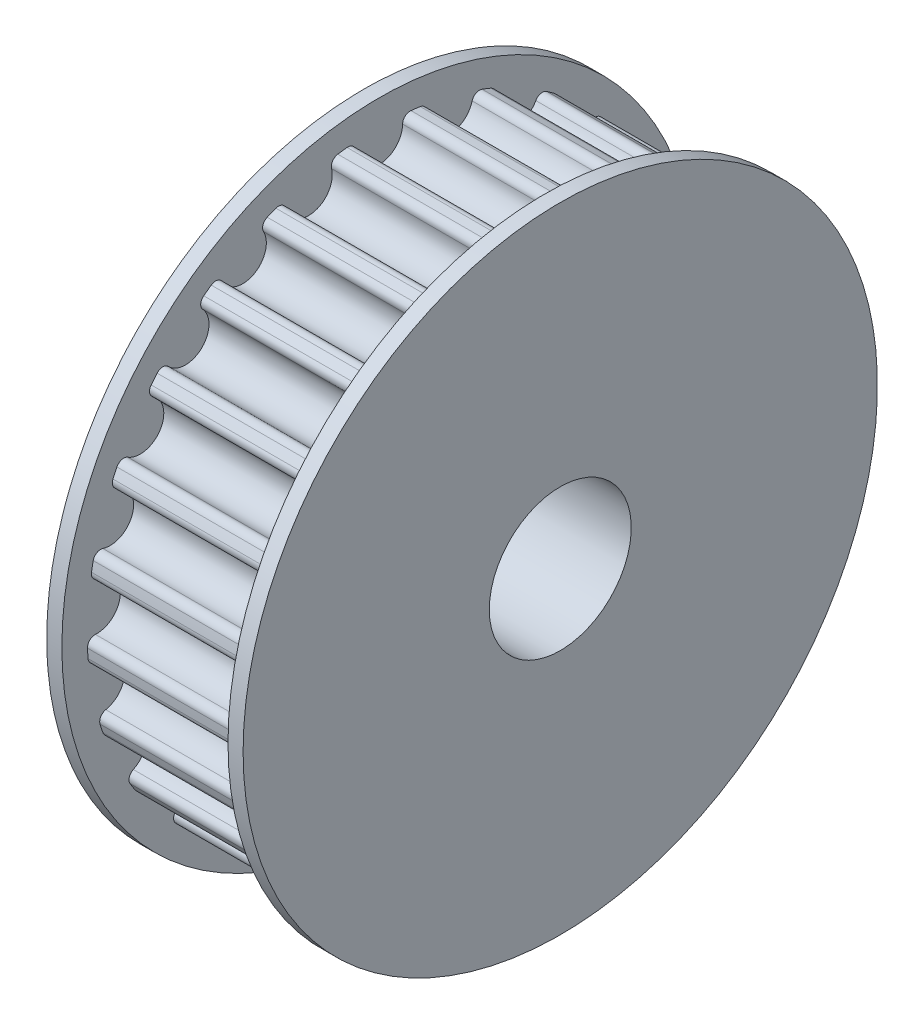
SolidWorks part; units mm, degrees
ref_plane "前视基准面" through (0, 0, 0) normal (0, 0, 1) x (1, 0, 0)
ref_plane "上视基准面" through (0, 0, 0) normal (0, 1, 0) x (1, 0, 0)
ref_plane "右视基准面" through (0, 0, 0) normal (1, 0, 0) x (0, 0, -1)
sketch "草图1" plane through (0, 0, 0) normal (0, 0, 1) x (1, 0, 0)
  line L0 (-8, 15) -> (-5.5, 15)
  line L1 (-5.5, 15) -> (-5.5, 19.325)
  line L2 (-5.5, 19.325) -> (5.5, 19.325)
  line L3 (0, 0) -> (0, 19.325) construction
  line L4 (-8, 15) -> (-8, 0)
  line L5 (8, 15) -> (8, 0)
  line L6 (5.5, 15) -> (5.5, 19.325)
  line L7 (8, 15) -> (5.5, 15)
  line L8 (-8, 0) -> (8, 0)
  dimension "D1" = 15
  dimension "D2" = 19.325
  dimension "D3" = 11
  dimension "D4" = 16
revolve "旋转1" add sketch "草图1" angle 360 about L8
sketch "草图3" plane through (0, 0, 0) normal (1, 0, 0) x (0, 0, -1)
  line L0 (0, 0) -> (0, 19.325) construction
  arc A0 (-2.1147, 19.209) -> (2.1147, 19.209) centre (0, 0) ccw
  circle A1 centre (0, 0) radius 19.325 construction
  arc A2 (-1.56, 18.7151) -> (1.56, 18.7151) centre (0, 18.725) ccw
  arc A3 (-1.56, 18.7151) -> (-2.1147, 19.209) centre (-2.06, 18.712) ccw
  arc A4 (2.1147, 19.209) -> (1.56, 18.7151) centre (2.06, 18.712) ccw
  point P5 (0, 17.165)
  point P11 (-1.4618, 19.2696)
  dimension "D4" = 0.5
  dimension "D1" = 2.16
  dimension "D2" = 1.56
  dimension "D5" = 0.5
extrude "切除-拉伸3" cut sketch "草图3" against normal mid plane 11 flip side to cut
pattern_circular "阵列(圆周)2" count 25 over 360 about axis through (0, 0, 0) along (1, 0, 0) of "切除-拉伸3"
sketch "草图4" plane through (0, 0, 0) normal (0, 0, 1) x (1, 0, 0)
  line L0 (-7, 22.5) -> (-7, 15)
  line L1 (-5.5, 15) -> (-8, 15) construction
  line L2 (7, 22.5) -> (7, 15)
  line L3 (-7, 22.5) -> (-5.9019, 22.5)
  line L4 (-5.9019, 22.5) -> (-5.5, 21)
  line L5 (-5.5, 21) -> (-5.5, 15)
  line L6 (-5.5, 15) -> (-7, 15)
  line L9 (0, 0) -> (0, 9.52) construction
  line L11 (-8, 0) -> (8, 0) construction
  line L12 (-8, 15) -> (-8, -15) construction
  line L13 (8, -15) -> (8, 15) construction
  line L14 (5.5, 21) -> (5.5, 15)
  line L15 (5.5, 15) -> (7, 15)
  line L17 (5.9019, 22.5) -> (5.5, 21)
  line L18 (7, 22.5) -> (5.9019, 22.5)
  dimension "D1" = 1.5
  dimension "D2" = 15
  dimension "D3" = 22.5
  dimension "D4" = 1.5
  dimension "D5" = 5.5
revolve "旋转2" add sketch "草图4" angle 360 about L11
sketch "草图5" plane through (0, 0, 0) normal (0, 0, 1) x (1, 0, 0)
  line L0 (8, -15) -> (8, 15) construction
  line L1 (8, 0) -> (20, 0)
  line L2 (8, 0) -> (8, 13.5)
  line L3 (8, 13.5) -> (20, 13.5)
  line L4 (20, 0) -> (20, 13.5)
  dimension "D1" = 13.5
  dimension "D2" = 12
revolve "旋转3" [suppressed] add sketch "草图5" angle 360 about L1
sketch "草图37" [suppressed] plane through (0, 0, 0) normal (0, 0, 1) x (1, 0, 0)
  line L0 (-8, 0) -> (8, 0) construction
  line L1 (-7.5, 13) -> (-5.5, 13)
  line L2 (-7.5, 13) -> (-7.5, 8)
  line L3 (-7.5, 8) -> (-5.5, 8)
  line L4 (-5.5, 13) -> (-5.5, 8)
  line L5 (-8, 8) -> (-8, -8) construction
  line L6 (8, -8) -> (8, 8) construction
  line L7 (0, 0) -> (0, 7.8967) construction
  line L8 (5.5, 13) -> (5.5, 8)
  line L9 (7.5, 8) -> (5.5, 8)
  line L10 (7.5, 13) -> (5.5, 13)
  line L11 (7.5, 13) -> (7.5, 8)
  dimension "D1" = 5.5
  dimension "D2" = 15
  dimension "D3" = 22.5
  dimension "D4" = 2
revolve "切除-旋转5" [suppressed] cut sketch "草图37" angle 360 about L0
sketch "草图7" plane through (-8, 0, 0) normal (-1, 0, 0) x (0, 0, 1)
  circle A0 centre (0, 0) radius 5
  dimension "D1" = 10
extrude "切除-拉伸4" cut sketch "草图7" against normal through all
sketch "草图38" [suppressed] plane through (0, 0, 0) normal (0, 1, 0) x (1, 0, 0)
  circle A0 centre (0, 0) radius 1.29
  dimension "D1" = 3.44
sketch "草图39" [suppressed] plane through (0, 0, 0) normal (0, 1, 0) x (1, 0, 0)
  line L0 (-8, 0) -> (8, 0) construction
  line L1 (-8, 8) -> (-8, -8) construction
  line L2 (8, -8) -> (8, 8) construction
ref_plane "基准面6" [suppressed] through (0, 0, 0) normal (0, -0.5, 0.866) x (1, 0, 0)
sketch "草图40" [suppressed] plane through (0, 0, 0) normal (0, -0.5, 0.866) x (1, 0, 0)
  circle A0 centre (0, 0) radius 1.29
  dimension "D1" = 3.44
sketch "草图31" [suppressed] plane through (0, 0, 0) normal (0, 1, 0) x (1, 0, 0)
  line L0 (-8, 8) -> (-8, -8) construction
  circle A0 centre (13, 0) radius 1.29
  dimension "D2" = 3.44
  dimension "D1" = 21
extrude "切除-拉伸21" [suppressed] cut sketch "草图31" along normal through all
cosmetic thread "装饰螺纹线9" [suppressed] parameters "D2"=4
sketch "草图32" [suppressed] plane through (0, 0, 0) normal (0, 1, 0) x (1, 0, 0)
  line L0 (0, 0) -> (-8, 0) construction
  line L1 (-8, 8) -> (-8, -8) construction
ref_plane "基准面5" [suppressed] through (0, 0, 0) normal (0, -0.5, -0.866) x (1, 0, 0)
sketch "草图33" [suppressed] plane through (0, 0, 0) normal (0, -0.5, -0.866) x (1, 0, 0)
  line L0 (-8, 8) -> (-8, -8) construction
  circle A0 centre (13, 0) radius 1.29
  dimension "D2" = 3.44
  dimension "D1" = 21
extrude "切除-拉伸22" [suppressed] cut sketch "草图33" along normal through all
cosmetic thread "装饰螺纹线10" [suppressed] parameters "D2"=4
sketch "草图16" [suppressed] plane through (-8, 0, 0) normal (-1, 0, 0) x (0, 0, 1)
  line L0 (-1.5, 0) -> (-1.5, 2.9)
  line L1 (-1.5, 2.9) -> (1.5, 2.9)
  line L2 (1.5, 2.9) -> (1.5, 0)
  arc A0 (-1.5, 0) -> (1.5, 0) centre (0, 0) ccw
  dimension "D2" = 5
  dimension "D1" = 3
  dimension "D3" = 6.4
extrude "切除-拉伸10" [suppressed] cut sketch "草图16" against normal through all
sketch "草图27" [suppressed] plane through (15, 0, 0) normal (1, 0, 0) x (0, 0, -1)
  circle A0 centre (0, 0) radius 5
  dimension "D1" = 10
extrude "切除-拉伸19" [suppressed] cut sketch "草图27" against normal blind 5
sketch "草图29" [suppressed] plane through (0, 0, 0) normal (0, 0, 1) x (1, 0, 0)
  line L0 (-8, 4.5) -> (-5, 4.5)
  line L1 (-8, 8) -> (-8, -8) construction
  line L2 (-5, 4.5) -> (-5, 1.5)
  line L3 (-5, 1.5) -> (5, 1.5)
  line L4 (5, 1.5) -> (5, 5)
  line L5 (5, 5) -> (8, 5)
  line L6 (8, -8) -> (8, 8) construction
  line L7 (8, 5) -> (8, 0)
  line L8 (8, 0) -> (-8, 0)
  line L9 (-8, 0) -> (-8, 4.5)
  dimension "D1" = 4.5
  dimension "D2" = 3
  dimension "D3" = 3
  dimension "D4" = 5
  dimension "D5" = 5
revolve "切除-旋转1" [suppressed] cut sketch "草图29" angle 360 about L8
sketch "草图36" [suppressed] plane through (0, 0, 0) normal (0, 0, 1) x (1, 0, 0)
  line L0 (0, 0) -> (-5, 0) construction
  line L1 (-3, 4.275) -> (-5, 4.275)
  line L2 (-3, 4.275) -> (-3, 5.95)
  line L3 (-3, 5.95) -> (-5, 5.95)
  line L4 (-5, 4.275) -> (-5, 5.95)
  line L5 (-5, 3) -> (-5, -3) construction
  dimension "D1" = 19.325
  dimension "D2" = 22.5
  dimension "D3" = 5.5
  dimension "D4" = 2
revolve "切除-旋转4" [suppressed] cut sketch "草图36" angle 360 about L0
sketch "草图35" [suppressed] plane through (0, 0, 0) normal (0, 0, 1) x (1, 0, 0)
  line L0 (-5, 0) -> (0, 0) construction
  line L1 (3, 4.275) -> (5, 4.275)
  line L2 (3, 4.275) -> (3, 5.95)
  line L3 (3, 5.95) -> (5, 5.95)
  line L4 (5, 4.275) -> (5, 5.95)
  line L5 (-5, 3) -> (-5, -3) construction
  dimension "D1" = 19.325
  dimension "D2" = 22.5
  dimension "D3" = 2
  dimension "D4" = 5.5
revolve "切除-旋转3" [suppressed] cut sketch "草图35" angle 360 about L0
extrude "切除-拉伸23" [suppressed] cut sketch "草图38" along normal through all
cosmetic thread "装饰螺纹线12" [suppressed] parameters "D2"=4
extrude "切除-拉伸24" [suppressed] cut sketch "草图40" along normal through all
cosmetic thread "装饰螺纹线11" [suppressed] parameters "D2"=4
sketch "草图41" [suppressed] plane through (0, 0, 0) normal (0, 0, 1) x (1, 0, 0)
  line L0 (-8, 8) -> (-8, -8) construction
  line L1 (-8, 0) -> (-3, 0)
  line L2 (-8, 0) -> (-8, 5)
  line L3 (-8, 5) -> (-3, 5)
  line L4 (-3, 0) -> (-3, 5)
  dimension "D1" = 5
  dimension "D2" = 5
revolve "切除-旋转6" [suppressed] cut sketch "草图41" angle 360 about L1
sketch "草图42" plane through (0, 0, 0) normal (0, 1, 0) x (1, 0, 0)
  line L0 (-7, 22.5) -> (-7, -22.5) construction
  line L1 (-6.5, 30.5282) -> (-18.1909, 30.5282)
  line L2 (-6.5, 30.5282) -> (-6.5, -24.9359)
  line L3 (-6.5, -24.9359) -> (-18.1909, -24.9359)
  line L4 (-18.1909, 30.5282) -> (-18.1909, -24.9359)
  line L5 (6.5, 32.7241) -> (24.4033, 32.7241)
  line L6 (6.5, 32.7241) -> (6.5, -23.2621)
  line L7 (6.5, -23.2621) -> (24.4033, -23.2621)
  line L8 (24.4033, 32.7241) -> (24.4033, -23.2621)
  line L9 (7, -22.5) -> (7, 22.5) construction
  point P10 (7, 15)
  point P11 (0, 0)
  point P12 (0, 0)
  dimension "D1" = 0.5
  dimension "D2" = 0.5
extrude "切除-拉伸25" cut sketch "草图42" against normal through all both and the other way through all
sketch "草图43" plane through (-6.5, 0, 0) normal (-1, 0, 0) x (0, 0, 1)
  circle A0 centre (0, 0) radius 21
  circle A1 centre (0, 0) radius 22.5
  dimension "D1" = 42
extrude "切除-拉伸27" cut sketch "草图43" against normal through all both and the other way through all
sketch "草图44" plane through (-6.5, 0, 0) normal (-1, 0, 0) x (0, 0, 1)
  circle A0 centre (0, 0) radius 5
  circle A1 centre (0, 0) radius 4.7
  dimension "D1" = 9.4
extrude "凸台-拉伸1" add sketch "草图44" against normal up to surface (13 mm away) up to face at (6.5, 0, 5)
